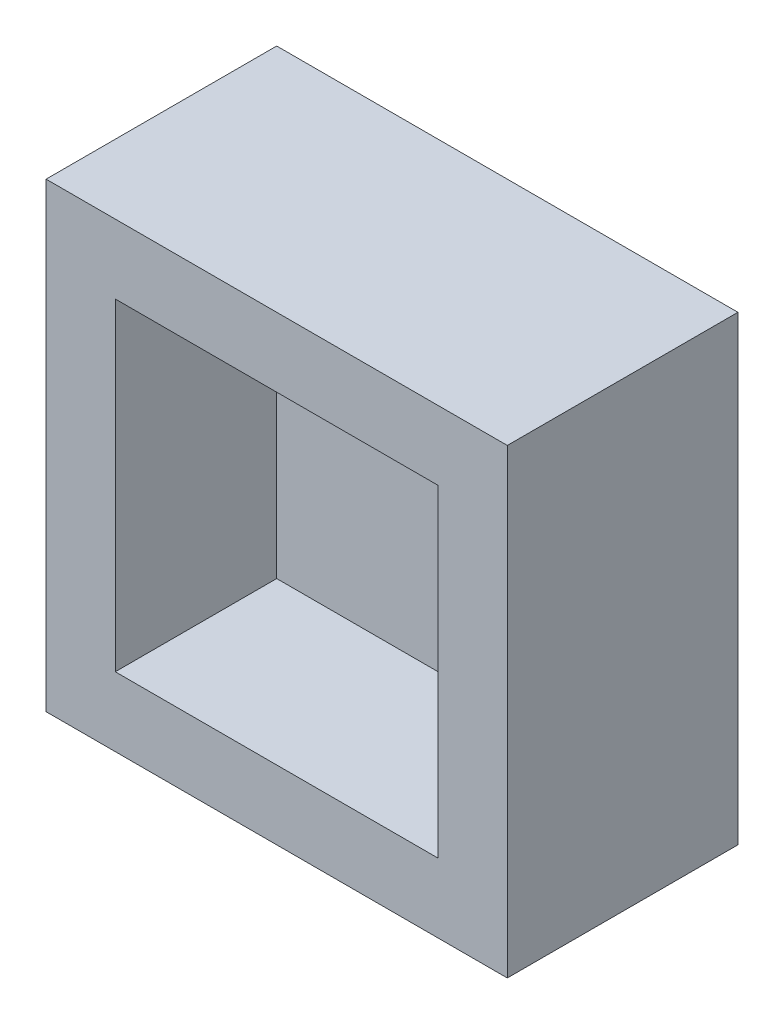
SolidWorks part; units mm, degrees
ref_plane "前视基准面" through (0, 0, 0) normal (0, 0, 1) x (1, 0, 0)
ref_plane "上视基准面" through (0, 0, 0) normal (0, 1, 0) x (1, 0, 0)
ref_plane "右视基准面" through (0, 0, 0) normal (1, 0, 0) x (0, 0, -1)
other "Configuration Table"
sketch "草图1" plane through (0, 0, 0) normal (0, 0, 1) x (1, 0, 0)
  line L1 (0, 0) -> (20, 0)
  line L2 (0, 0) -> (0, 20)
  line L3 (0, 20) -> (20, 20)
  line L4 (20, 0) -> (20, 20)
extrude "BaseBox" add sketch "草图1" along normal blind 10
shell "Shell" thickness 3
